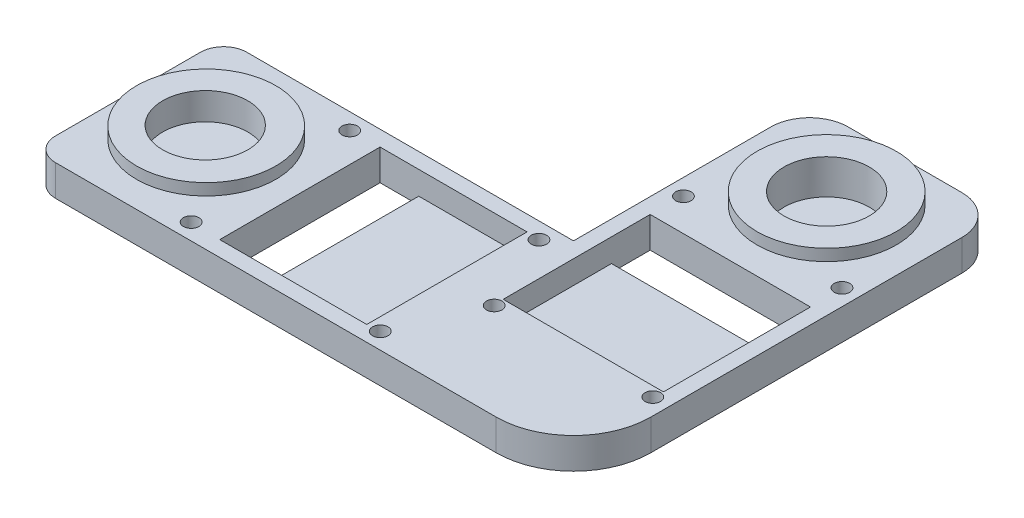
SolidWorks part; units mm, degrees
ref_plane "前视基准面" through (0, 0, 0) normal (0, 0, 1) x (1, 0, 0)
ref_plane "上视基准面" through (0, 0, 0) normal (0, 1, 0) x (1, 0, 0)
ref_plane "右视基准面" through (0, 0, 0) normal (1, 0, 0) x (0, 0, -1)
other "Configuration Table"
ref_plane "基准面1" through (0, 0, 0) normal (0, 1, 0) x (1, 0, 0)
sketch "草图1" plane through (0, 0, 0) normal (0, 1, 0) x (1, 0, 0)
  line L0 (6.61, -12.36) -> (9.61, -12.36)
  line L1 (-32.61, -12.36) -> (6.61, -12.36)
  line L2 (-35.61, -9.36) -> (-35.61, 9.36)
  line L3 (-32.61, 12.36) -> (6.61, 12.36)
  line L4 (9.61, -9.36) -> (9.61, 9.36)
  line L5 (9.61, -12.36) -> (9.61, -9.36)
  line L6 (6.61, 12.36) -> (9.61, 12.36)
  line L7 (9.61, 12.36) -> (9.61, 9.36)
  arc A1 (-32.61, 12.36) -> (-35.61, 9.36) centre (-32.61, 9.36) ccw
  arc A2 (-35.61, -9.36) -> (-32.61, -12.36) centre (-32.61, -9.36) ccw
extrude "凸台-拉伸1" add sketch "草图1" along normal blind 4
sketch "草图2" plane through (0, 0, 0) normal (0, 1, 0) x (1, 0, 0)
  circle A0 centre (7.25, -10.25) radius 1
  circle A1 centre (7.25, 10.25) radius 1
  circle A2 centre (-17.2, -10.25) radius 1
  circle A3 centre (-17.2, 10.25) radius 1
  dimension "D1" = 2
  dimension "D2" = 2
  dimension "D3" = 2
  dimension "D4" = 2
extrude "切除-拉伸1" cut sketch "草图2" against normal through all and the other way through all
sketch "草图3" plane through (0, 4, 0) normal (0, 1, 0) x (1, 0, 0)
  line L0 (9.61, 12.36) -> (-32.61, 12.36) construction
  line L1 (-8.39, -10.36) -> (5.61, -10.36)
  line L2 (-8.39, -10.36) -> (-8.39, 10.36)
  line L3 (-8.39, 10.36) -> (5.61, 10.36)
  line L4 (5.61, -10.36) -> (5.61, 10.36)
  line L9 (9.61, -12.36) -> (9.61, 12.36) construction
  line L10 (-32.61, -12.36) -> (9.61, -12.36) construction
  dimension "D1" = 2
  dimension "D2" = 4
  dimension "D3" = 2
  dimension "D4" = 14
extrude "切除-拉伸3" cut sketch "草图3" against normal blind 3
sketch "草图5" plane through (0, 4, 0) normal (0, 1, 0) x (1, 0, 0)
  line L0 (9.61, 12.36) -> (-32.61, 12.36) construction
  line L1 (-13.39, 10.36) -> (-8.39, 10.36)
  line L2 (-13.39, 10.36) -> (-13.39, -10.36)
  line L3 (-13.39, -10.36) -> (-8.39, -10.36)
  line L4 (-8.39, 10.36) -> (-8.39, -10.36)
  line L5 (-8.39, 10.36) -> (-8.39, -10.36) construction
  line L6 (-32.61, -12.36) -> (9.61, -12.36) construction
  dimension "D1" = 2
  dimension "D2" = 0
  dimension "D3" = 2
  dimension "D4" = 5
extrude "切除-拉伸4" cut sketch "草图5" against normal blind 4
sketch "草图6" plane through (0, 4, 0) normal (0, 1, 0) x (1, 0, 0)
  line L0 (9.61, -12.36) -> (9.61, 12.36) construction
  circle A0 centre (-25.5, 0) radius 9
  dimension "D2" = 18
  dimension "D1" = 35.11
extrude "凸台-拉伸2" add sketch "草图6" along normal blind 1.5
sketch "草图10" plane through (0, 5.5, 0) normal (0, 1, 0) x (1, 0, 0)
  line L0 (9.61, 12.36) -> (-32.61, 12.36) construction
  circle A0 centre (-25.6224, 0) radius 5.5
  dimension "D1" = 11
  dimension "D2" = 12.36
extrude "切除-拉伸6" cut sketch "草图10" against normal blind 3.5
sketch "草图11" plane through (0, 0, 0) normal (0, -1, 0) x (1, 0, 0)
  line L0 (-32.61, 12.36) -> (9.61, 12.36) construction
  circle A0 centre (-26.9304, 0) radius 4.75
  dimension "D2" = 9.5
  dimension "D1" = 12.36
sketch "草图12" plane through (9.61, 0, 0) normal (1, 0, 0) x (0, 0, -1)
  line L4 (-12.36, 0) -> (12.36, 0)
  line L5 (12.36, 0) -> (12.36, 4)
  line L6 (12.36, 4) -> (-12.36, 4)
  line L7 (-12.36, 4) -> (-12.36, 0)
  line L8 (-12.36, 0) -> (12.36, 0)
  line L9 (12.36, 0) -> (12.36, 4)
  line L10 (12.36, 4) -> (-12.36, 4)
  line L11 (-12.36, 4) -> (-12.36, 0)
  dimension "D1" = 0
extrude "凸台-拉伸3" add sketch "草图12" along normal blind 24.72
sketch "草图14" plane through (0, 0, -12.36) normal (0, 0, -1) x (-1, 0, 0)
  line L0 (-34.33, 0) -> (-34.33, 4) construction
  line L1 (-34.33, 4) -> (-9.61, 4)
  line L2 (-34.33, 4) -> (-34.33, 0)
  line L3 (-34.33, 0) -> (-9.61, 0)
  line L4 (-9.61, 4) -> (-9.61, 0)
  line L5 (-34.33, 4) -> (32.61, 4) construction
  dimension "D1" = 24.72
  dimension "D2" = 4
  dimension "D3" = 0
  dimension "D4" = 0
extrude "凸台-拉伸4" add sketch "草图14" along normal blind 30.5
sketch "草图15" plane through (0, 4, 0) normal (0, 1, 0) x (1, 0, 0)
  line L0 (9.61, 42.86) -> (34.33, 42.86) construction
  line L1 (9.61, 42.86) -> (9.61, 12.36) construction
  line L2 (34.33, 42.86) -> (34.33, -12.36) construction
  circle A0 centre (11.72, 24.45) radius 1
  circle A1 centre (32.22, 24.45) radius 1
  circle A2 centre (11.72, 0) radius 1
  circle A3 centre (32.22, 0) radius 1
  circle A4 centre (21.9389, 32.75) radius 9
  circle A5 centre (21.9389, 32.75) radius 5.5
  dimension "D1" = 2
  dimension "D2" = 2
  dimension "D3" = 2
  dimension "D4" = 2
  dimension "D7" = 20.5
  dimension "D8" = 2.11
  dimension "D9" = 24.45
  dimension "D11" = 2.11
  dimension "D12" = 20.5
  dimension "D14" = 18
  dimension "D15" = 11
  dimension "D5" = 18.41
  dimension "D6" = 18.41
  dimension "D10" = 24.45
  dimension "D13" = 10.11
extrude "切除-拉伸7" cut sketch "草图15" against normal blind 4 contours A5 | A2 | A3 | A1 | A0
sketch "草图16" plane through (0, 4, 0) normal (0, 1, 0) x (1, 0, 0)
  circle A0 centre (21.9389, 32.75) radius 9
  circle A1 centre (21.9389, 32.75) radius 5.5
  dimension "D1" = 18
  dimension "D2" = 11
extrude "凸台-拉伸5" add sketch "草图16" along normal blind 1.5
sketch "草图17" plane through (0, 4, 0) normal (0, 1, 0) x (1, 0, 0)
  line L0 (9.61, 42.86) -> (9.61, 12.36) construction
  line L1 (11.61, 20.27) -> (32.33, 20.27)
  line L2 (11.61, 20.27) -> (11.61, 1.27)
  line L3 (11.61, 1.27) -> (32.33, 1.27)
  line L4 (32.33, 20.27) -> (32.33, 1.27)
  line L5 (9.61, 42.86) -> (34.33, 42.86) construction
  dimension "D1" = 20.72
  dimension "D2" = 19
  dimension "D3" = 22.59
  dimension "D4" = 2
extrude "切除-拉伸8" cut sketch "草图17" against normal blind 4
sketch "草图19" plane through (0, 0, 0) normal (0, -1, 0) x (1, 0, 0)
  line L0 (11.61, -1.27) -> (32.33, -1.27) construction
  line L1 (11.61, -1.27) -> (32.33, -1.27)
  line L2 (11.61, -1.27) -> (11.61, -15.27)
  line L3 (11.61, -15.27) -> (32.33, -15.27)
  line L4 (32.33, -1.27) -> (32.33, -15.27)
  line L5 (11.61, -20.27) -> (11.61, -1.27) construction
  line L6 (32.33, -1.27) -> (32.33, -20.27) construction
  dimension "D1" = 14
  dimension "D2" = 0
  dimension "D3" = 0
extrude "凸台-拉伸6" add sketch "草图19" against normal blind 1
sketch "草图20" plane through (0, 0, 0) normal (0, -1, 0) x (1, 0, 0)
  circle A0 centre (21.9389, -32.75) radius 5.5
extrude "凸台-拉伸7" add sketch "草图20" against normal blind 1
fillet "圆角1" radius 5 1 edges at (34.33, 2, -42.86)
fillet "圆角2" radius 5 1 edges at (9.61, 2, -42.86)
fillet "圆角6" radius 10 1 edges at (34.33, 2, 12.36)
